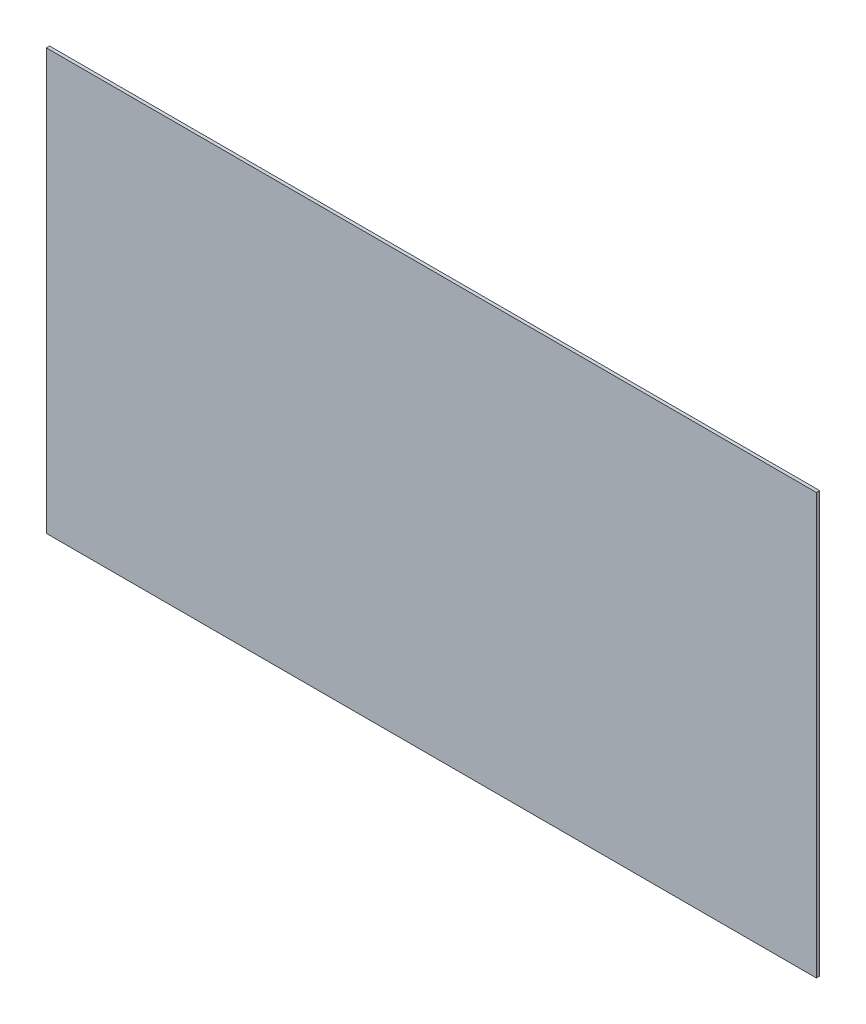
SolidWorks part; units mm, degrees
ref_plane "Front Plane" through (0, 0, 0) normal (0, 0, 1) x (1, 0, 0)
ref_plane "Top Plane" through (0, 0, 0) normal (0, 1, 0) x (1, 0, 0)
ref_plane "Right Plane" through (0, 0, 0) normal (1, 0, 0) x (0, 0, -1)
sketch "Sketch1" plane through (0, 0, 0) normal (0, 0, 1) x (1, 0, 0)
  line L1 (-27.051, 6.35) -> (-785.749, 6.35)
  line L2 (-27.051, 6.35) -> (-27.051, 420.6875)
  line L3 (-27.051, 420.6875) -> (-785.749, 420.6875)
  line L4 (-785.749, 6.35) -> (-785.749, 420.6875)
extrude "Boss-Extrude1" add sketch "Sketch1" along normal blind 3.175 contours L3 L4 L1 L2
